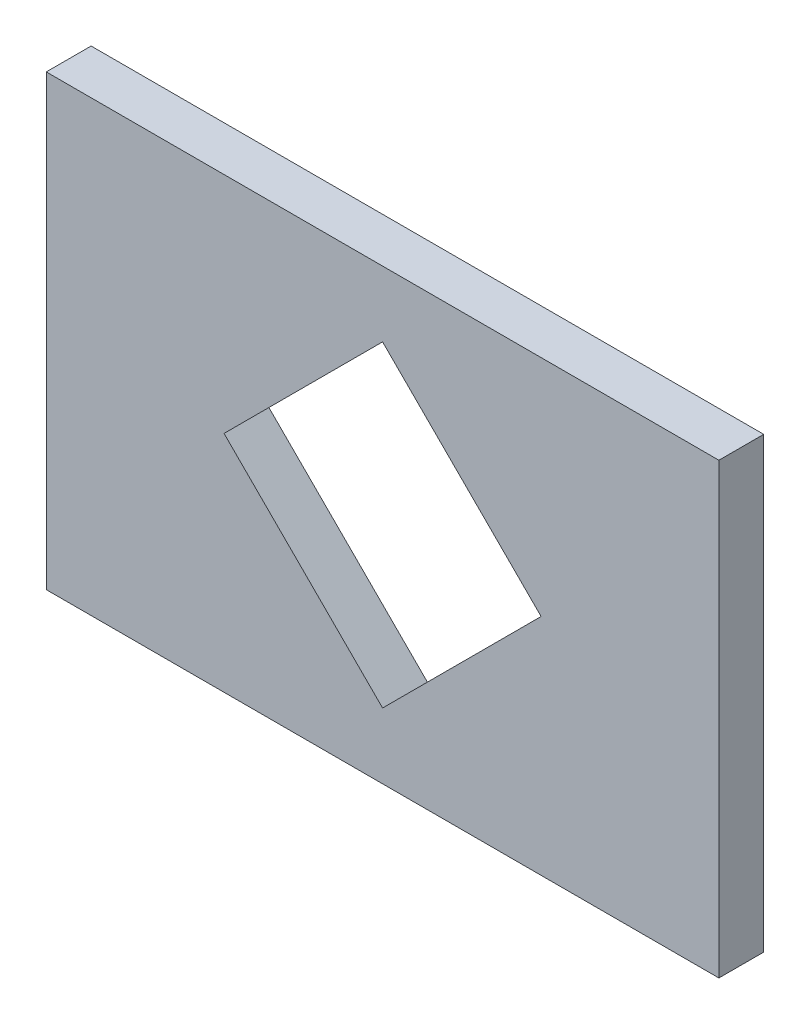
SolidWorks part; units mm, degrees
ref_plane "Front Plane" through (0, 0, 0) normal (0, 0, 1) x (1, 0, 0)
ref_plane "Top Plane" through (0, 0, 0) normal (0, 1, 0) x (1, 0, 0)
ref_plane "Right Plane" through (0, 0, 0) normal (1, 0, 0) x (0, 0, -1)
sketch "Sketch2" plane through (0, 0, 0) normal (0, 0, 1) x (1, 0, 0)
  line L1 (-75, 50) -> (75, 50)
  line L2 (-75, 50) -> (-75, -50)
  line L3 (-75, -50) -> (75, -50)
  line L4 (75, 50) -> (75, -50)
  line L5 (-75, 50) -> (75, -50) construction
  line L6 (-75, -50) -> (75, 50) construction
  line L7 (0, -35.3553) -> (35.3553, 0)
  line L8 (35.3553, 0) -> (0, 35.3553)
  line L9 (0, 35.3553) -> (-35.3553, 0)
  line L10 (-35.3553, 0) -> (0, -35.3553)
  circle A0 centre (0, 0) radius 25 construction
  point P0 (0, 0)
  dimension "D3" = 50
  dimension "D1" = 100
  dimension "D2" = 150
extrude "Boss-Extrude1" add sketch "Sketch2" along normal blind 10
